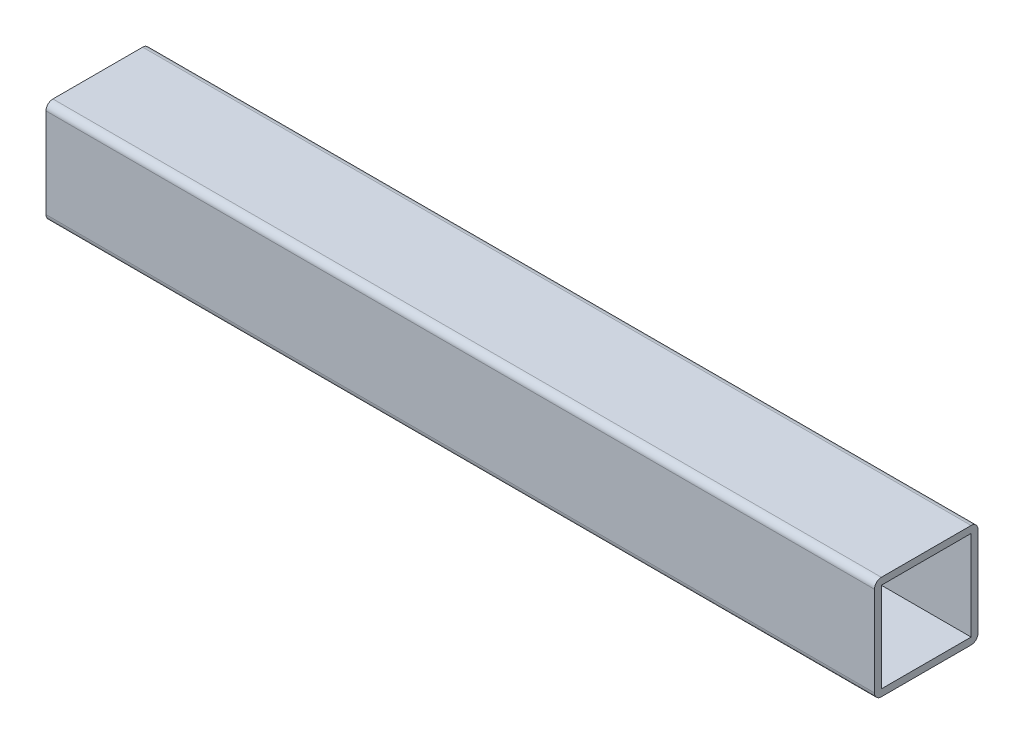
SolidWorks part; units mm, degrees
ref_plane "Front Plane" through (0, 0, 0) normal (0, 0, 1) x (1, 0, 0)
ref_plane "Top Plane" through (0, 0, 0) normal (0, 1, 0) x (1, 0, 0)
ref_plane "Right Plane" through (0, 0, 0) normal (1, 0, 0) x (0, 0, -1)
sketch "Sketch1" plane through (0, 0, 0) normal (1, 0, 0) x (0, 0, -1)
  line L0 (10, 10) -> (10, 140)
  line L1 (10, 0) -> (140, 0)
  line L2 (0, 10) -> (0, 140)
  line L3 (10, 150) -> (140, 150)
  line L4 (150, 10) -> (150, 140)
  line L5 (10, 10) -> (140, 10)
  line L6 (140, 10) -> (140, 140)
  line L7 (10, 140) -> (140, 140)
  arc A0 (0, 140) -> (10, 150) centre (10, 140) cw
  arc A1 (150, 140) -> (140, 150) centre (140, 140) ccw
  arc A2 (10, 0) -> (0, 10) centre (10, 10) cw
  arc A3 (140, 0) -> (150, 10) centre (140, 10) ccw
  point P6 (0, 150)
  point P9 (150, 150)
  point P12 (0, 0)
  dimension "D3" = 10
  dimension "Width" = 150
  dimension "D2" = 150
extrude "Extrude1" add sketch "Sketch1" along normal blind 1200
